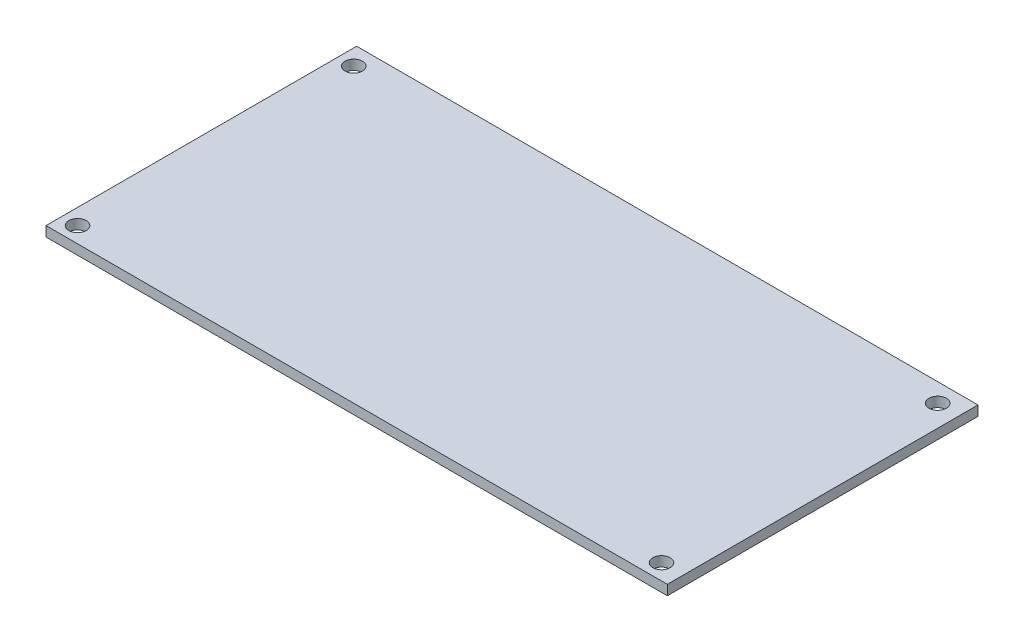
SolidWorks part; units mm, degrees
ref_plane "Front Plane" through (0, 0, 0) normal (0, 0, 1) x (1, 0, 0)
ref_plane "Top Plane" through (0, 0, 0) normal (0, 1, 0) x (1, 0, 0)
ref_plane "Right Plane" through (0, 0, 0) normal (1, 0, 0) x (0, 0, -1)
sketch "Sketch1" plane through (0, 0, 0) normal (0, 1, 0) x (1, 0, 0)
  line L1 (-37.9243, 26.1593) -> (62.0757, 26.1593)
  line L2 (-37.9243, 26.1593) -> (-37.9243, -23.8407)
  line L3 (-37.9243, -23.8407) -> (62.0757, -23.8407)
  line L4 (62.0757, 26.1593) -> (62.0757, -23.8407)
  circle A0 centre (-35.3843, 23.1493) radius 1.397
  circle A1 centre (-35.3843, -21.3007) radius 1.397
  circle A2 centre (58.5957, -21.3007) radius 1.397
  circle A3 centre (58.5957, 23.1493) radius 1.397
  dimension "D7" = 2.794
  dimension "D1" = 100
  dimension "D2" = 50
  dimension "D3" = 2.54
  dimension "D4" = 46.99
  dimension "D5" = 2.54
  dimension "D6" = 96.52
extrude "Boss-Extrude1" add sketch "Sketch1" along normal blind 1.6
